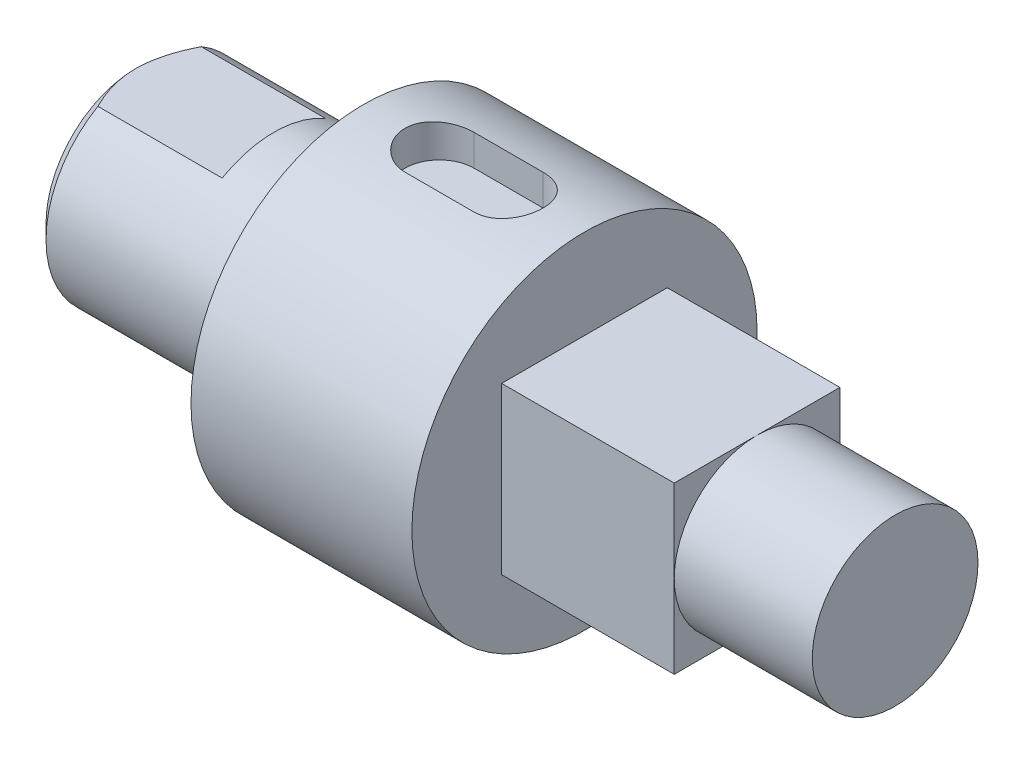
SolidWorks part; units mm, degrees
ref_plane "Front Plane" through (0, 0, 0) normal (0, 0, 1) x (1, 0, 0)
ref_plane "Top Plane" through (0, 0, 0) normal (0, 1, 0) x (1, 0, 0)
ref_plane "Right Plane" through (0, 0, 0) normal (1, 0, 0) x (0, 0, -1)
sketch "Sketch1" plane through (0, 0, 0) normal (1, 0, 0) x (0, 0, -1)
  circle A0 centre (0, 0) radius 25
  dimension "D1" = 50
extrude "Boss-Extrude1" add sketch "Sketch1" along normal blind 110
sketch "Sketch2" plane through (110, 0, 0) normal (1, 0, 0) x (0, 0, -1)
  line L0 (12, 0) -> (-12, 0) construction
  line L1 (0, -12) -> (0, 12) construction
  line L2 (12, 12) -> (-12, 12)
  line L3 (-12, 12) -> (-12, -12)
  line L4 (-12, -12) -> (12, -12)
  line L5 (12, -12) -> (12, 12)
  point P9 (0, 0)
  dimension "D1" = 24
extrude "Cut-Extrude1" cut sketch "Sketch2" against normal blind 45 flip side to cut
sketch "Sketch3" plane through (110, 0, 0) normal (1, 0, 0) x (0, 0, -1)
  circle A0 centre (0, 0) radius 12
  dimension "D1" = 24
extrude "Cut-Extrude2" cut sketch "Sketch3" against normal blind 20 flip side to cut
sketch "Sketch4" plane through (0, 0, 0) normal (-1, 0, 0) x (0, 0, 1)
  circle A0 centre (0, 0) radius 15
  dimension "D1" = 30
extrude "Cut-Extrude3" cut sketch "Sketch4" against normal blind 33 flip side to cut
chamfer "Chamfer1" distance 2 angle 45 1 edges at (0, 0, 15)
ref_plane "Plane1" through (0, 15, 0) normal (0, 1, 0) x (1, 0, 0)
sketch "Sketch5" plane through (0, 15, 0) normal (0, 1, 0) x (1, 0, 0)
  line L0 (0, 0) -> (33, 0) construction
  line L1 (33, 15) -> (33, -15) construction
  line L2 (0, 8) -> (20, 8)
  line L3 (0, 13) -> (0, -13) construction
  line L4 (20, 8) -> (20, -8)
  line L5 (20, -8) -> (0, -8)
  line L6 (0, -8) -> (0, 8)
  dimension "D1" = 20
  dimension "D2" = 16
extrude "Cut-Extrude4" cut sketch "Sketch5" against normal blind 2
ref_plane "Plane2" through (0, 25, 0) normal (0, 1, 0) x (1, 0, 0)
sketch "Sketch6" plane through (0, 25, 0) normal (0, 1, 0) x (1, 0, 0)
  line L0 (33, 0) -> (65, 0) construction
  line L1 (33, 15) -> (33, -15) construction
  line L2 (65, -25) -> (65, 25) construction
  line L3 (33, 25) -> (33, -25) construction
  line L4 (44, -5) -> (54, -5)
  line L5 (54, 5) -> (44, 5)
  arc A0 (44, 5) -> (44, -5) centre (44, 0) ccw
  arc A1 (54, -5) -> (54, 5) centre (54, 0) ccw
  dimension "D1" = 5
  dimension "D2" = 10
  dimension "D3" = 11
extrude "Cut-Extrude5" cut sketch "Sketch6" against normal blind 5
